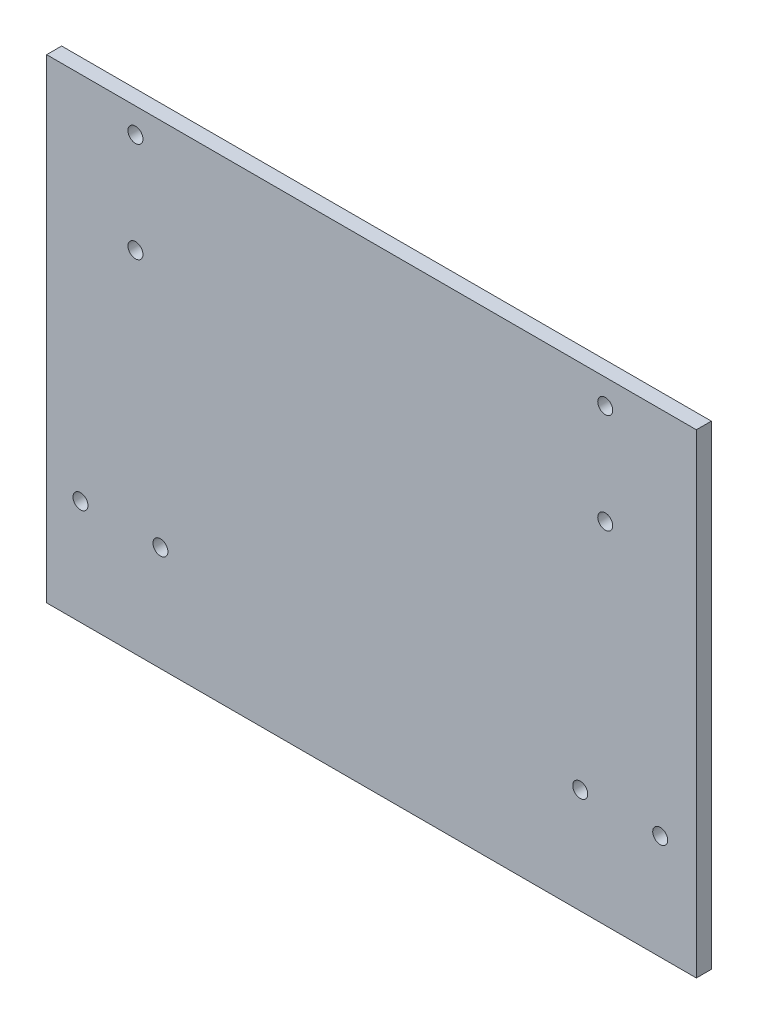
SolidWorks part; units mm, degrees
ref_plane "前视基准面" through (0, 0, 0) normal (0, 0, 1) x (1, 0, 0)
ref_plane "上视基准面" through (0, 0, 0) normal (0, 1, 0) x (1, 0, 0)
ref_plane "右视基准面" through (0, 0, 0) normal (1, 0, 0) x (0, 0, -1)
sketch "草图1" plane through (0, 0, 0) normal (0, 0, 1) x (1, 0, 0)
  line L1 (65, -47.5) -> (-65, -47.5)
  line L2 (65, -47.5) -> (65, 47.5)
  line L3 (65, 47.5) -> (-65, 47.5)
  line L4 (-65, -47.5) -> (-65, 47.5)
  line L5 (65, -47.5) -> (-65, 47.5) construction
  line L6 (65, 47.5) -> (-65, -47.5) construction
  point P0 (0, 0)
  dimension "D1" = 130
  dimension "D2" = 95
extrude "凸台-拉伸1" add sketch "草图1" along normal blind 3
sketch "草图2" plane through (0, 0, 3) normal (0, 0, 1) x (1, 0, 0)
  line L0 (0, -47.5) -> (0, -26.5) construction
  line L1 (-65, -47.5) -> (65, -47.5) construction
  line L2 (0, -26.5) -> (10, -26.5) construction
  circle A0 centre (10, -26.5) radius 1.5
  circle A1 centre (-10, -26.5) radius 1.5
  dimension "D3" = 3
  dimension "D1" = 21
  dimension "D2" = 10
sketch "草图3" plane through (0, 0, 0) normal (0, 0, -1) x (-1, 0, 0)
  circle A0 centre (-57.7671, -26.5) radius 1.5
  circle A1 centre (-41.7671, -26.5) radius 1.5
  circle A2 centre (42.2329, -26.5) radius 1.5
  circle A4 centre (58.2329, -26.5) radius 1.5
extrude "切除-拉伸2" cut sketch "草图3" against normal blind 10
sketch "草图4" plane through (0, 0, 0) normal (0, 0, -1) x (-1, 0, 0)
  circle A0 centre (-46.7671, 42.5) radius 1.5
  circle A1 centre (-46.7671, 22.5) radius 1.5
  circle A2 centre (47.2329, 42.5) radius 1.5
  circle A3 centre (47.2329, 22.5) radius 1.5
extrude "切除-拉伸3" cut sketch "草图4" against normal blind 10
